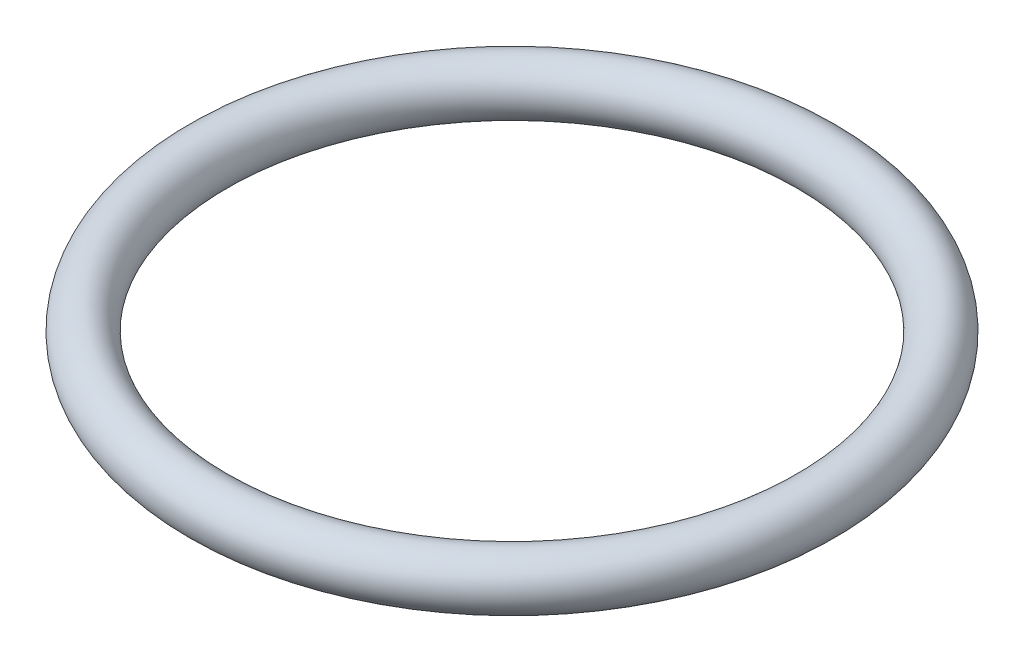
SolidWorks part; units mm, degrees
ref_plane "Front Plane" through (0, 0, 0) normal (0, 0, 1) x (1, 0, 0)
ref_plane "Top Plane" through (0, 0, 0) normal (0, 1, 0) x (1, 0, 0)
ref_plane "Right Plane" through (0, 0, 0) normal (1, 0, 0) x (0, 0, -1)
sketch "Sketch1" plane through (0, 0, 0) normal (0, 0, 1) x (1, 0, 0)
  line L0 (0, 0) -> (50000, 0) construction
  line L1 (0, 0) -> (0, 50000) construction
  circle A0 centre (10.2743, 0) radius 0.889
  point P6 (9.3853, 0)
  dimension "D1" = 1.778
  dimension "D2" = 9.3853
revolve "Revolve1" add sketch "Sketch1" angle 360 about L1
sketch "Sketch2" plane through (0, 0, 0) normal (0, 1, 0) x (1, 0, 0)
  circle A0 centre (0, 0) radius 11.1633
  circle A1 centre (0, 0) radius 11.1633 construction
